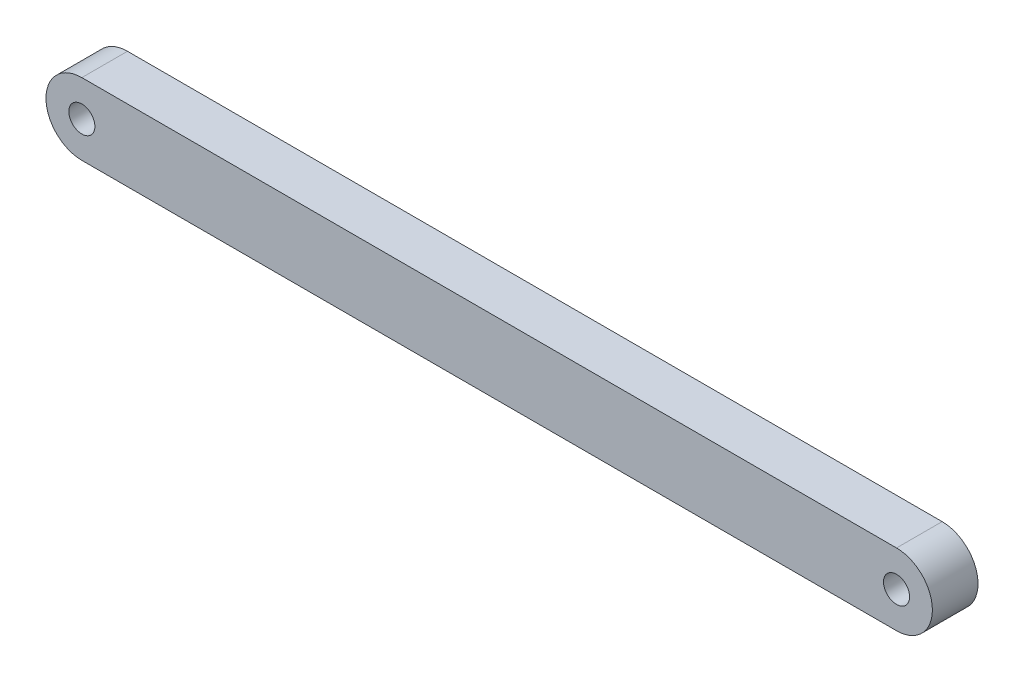
SolidWorks part; units mm, degrees
ref_plane "前视基准面" through (0, 0, 0) normal (0, 0, 1) x (1, 0, 0)
ref_plane "上视基准面" through (0, 0, 0) normal (0, 1, 0) x (1, 0, 0)
ref_plane "右视基准面" through (0, 0, 0) normal (1, 0, 0) x (0, 0, -1)
other "Configuration Table"
sketch "草图1" plane through (0, 0, 0) normal (0, 0, 1) x (1, 0, 0)
  line L0 (0, 0) -> (261, 0) construction
  line L1 (0, 11) -> (250, 11)
  line L2 (0, -11) -> (250, -11)
  arc A0 (0, 11) -> (0, -11) centre (0, 0) ccw
  arc A1 (250, -11) -> (250, 11) centre (250, 0) ccw
  point P3 (0, 0)
extrude "凸台-拉伸1" add sketch "草图1" along normal blind 14
sketch "草图2" plane through (0, 0, 0) normal (0, 0, 1) x (1, 0, 0)
  circle A0 centre (0, 0) radius 4
  circle A1 centre (250, 0) radius 4
extrude "切除-拉伸1" cut sketch "草图2" along normal blind 14
